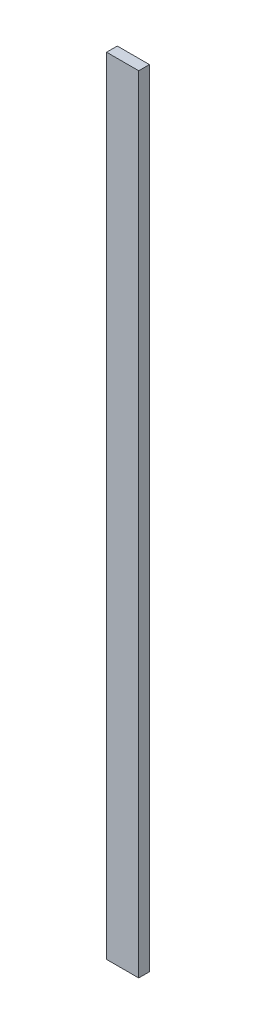
SolidWorks part; units mm, degrees
ref_plane "Front Plane" through (0, 0, 0) normal (0, 0, 1) x (1, 0, 0)
ref_plane "Top Plane" through (0, 0, 0) normal (0, 1, 0) x (1, 0, 0)
ref_plane "Right Plane" through (0, 0, 0) normal (1, 0, 0) x (0, 0, -1)
sketch "Sketch1" plane through (0, 0, 0) normal (0, 1, 0) x (1, 0, 0)
  line L1 (-2.25, 0.75) -> (2.25, 0.75)
  line L2 (-2.25, 0.75) -> (-2.25, -0.75)
  line L3 (-2.25, -0.75) -> (2.25, -0.75)
  line L4 (2.25, 0.75) -> (2.25, -0.75)
  line L5 (-2.25, 0.75) -> (2.25, -0.75) construction
  line L6 (-2.25, -0.75) -> (2.25, 0.75) construction
  point P0 (0, 0)
  dimension "D1" = 4.5
  dimension "D2" = 1.5
extrude "Boss-Extrude1" add sketch "Sketch1" along normal blind 110
